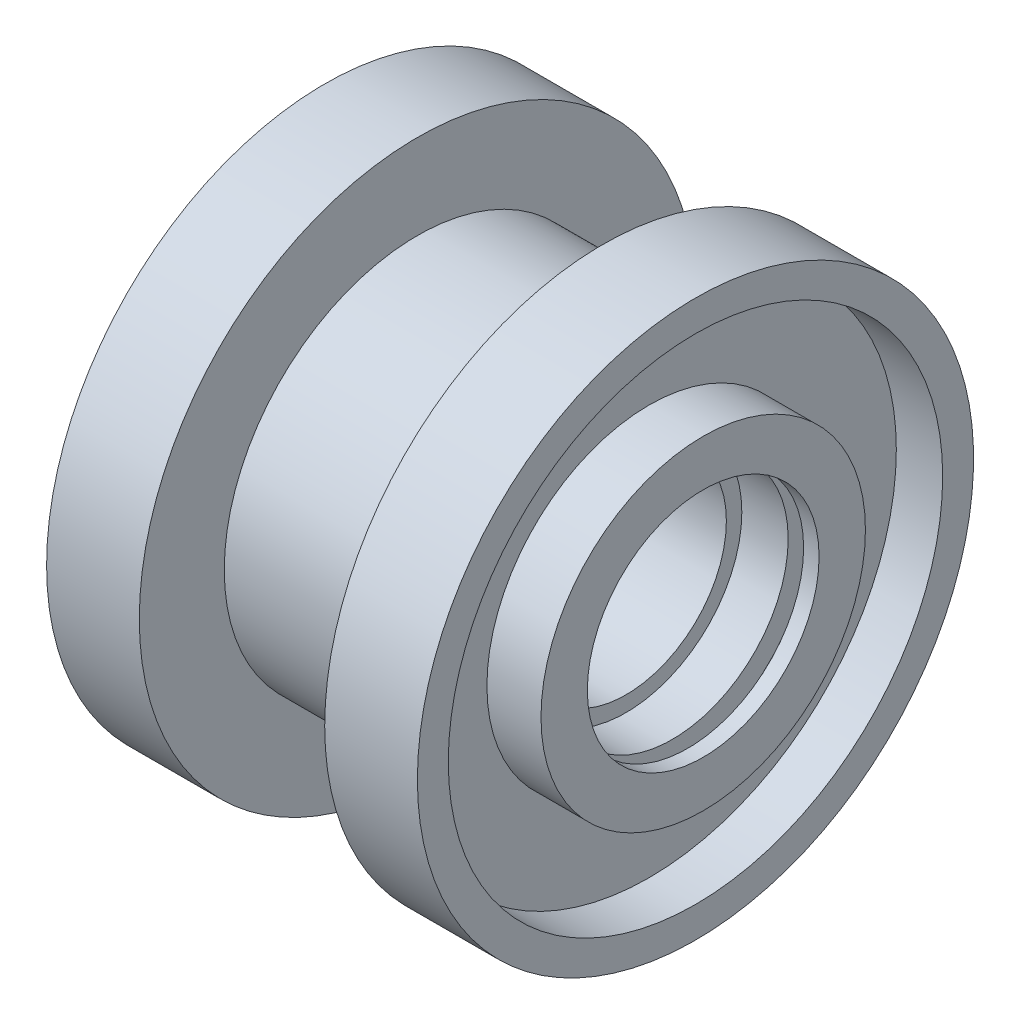
SolidWorks part; units mm, degrees
material "PS HI"
ref_plane "Płaszczyzna przednia" through (0, 0, 0) normal (0, 0, 1) x (1, 0, 0)
ref_plane "Płaszczyzna górna" through (0, 0, 0) normal (0, 1, 0) x (1, 0, 0)
ref_plane "Płaszczyzna prawa" through (0, 0, 0) normal (1, 0, 0) x (0, 0, -1)
sketch "Szkic1" plane through (0, 0, 0) normal (0, 0, 1) x (1, 0, 0)
  line L0 (-12.5, 0) -> (12.5, 0) construction
  line L1 (0, -18) -> (0, 18) construction
  line L2 (-6, 12.5) -> (6, 12.5)
  line L3 (6, 12.5) -> (6, 18)
  line L4 (6, 18) -> (12, 18)
  line L5 (12, 18) -> (12, 16)
  line L6 (12, 16) -> (9, 16)
  line L7 (9, 16) -> (9, 10.5)
  line L10 (-12, 16) -> (-9, 16)
  line L11 (-12, 18) -> (-12, 16)
  line L12 (-6, 18) -> (-12, 18)
  line L13 (-6, 12.5) -> (-6, 18)
  line L15 (12.5, 7.5) -> (12.5, 10.5)
  line L16 (12.5, 10.5) -> (9, 10.5)
  line L18 (-9, 16) -> (-9, 10.5)
  line L20 (-12.5, 7.5) -> (-12.5, 10.5)
  line L21 (-12.5, 10.5) -> (-9, 10.5)
  line L22 (12.5, 7.5) -> (11.5, 7.5)
  line L23 (7.5, 7.5) -> (7.5, 6.5)
  line L24 (7.5, 6.5) -> (-7.5, 6.5)
  line L25 (-7.5, 7.5) -> (-10.5, 7.5)
  line L26 (-7.5, 7.5) -> (-7.5, 6.5)
  line L27 (11.5, 7.5) -> (11.5, 8.9)
  line L28 (11.5, 8.9) -> (10.5, 8.9)
  line L29 (10.5, 8.9) -> (10.5, 7.5)
  line L30 (10.5, 7.5) -> (7.5, 7.5)
  line L31 (-11.5, 7.5) -> (-11.5, 8.9)
  line L32 (-10.5, 8.9) -> (-10.5, 7.5)
  line L33 (-11.5, 8.9) -> (-10.5, 8.9)
  line L34 (-11.5, 7.5) -> (-12.5, 7.5)
  point P1 (12, 17)
  point P7 (0, 0)
  point P14 (0, 7.5)
  point P15 (7.5, 7.5)
  point P21 (0, 12.5)
  point P23 (12.5, 9)
  point P32 (0, 6.5)
  dimension "D2" = 25
  dimension "D3" = 32
  dimension "D4" = 36
  dimension "D5" = 3
  dimension "D6" = 6
  dimension "D7" = 12
  dimension "D8" = 21
  dimension "D9" = 3.5
  dimension "D10" = 25
  dimension "D11" = 5
  dimension "D12" = 13
  dimension "D14" = 1
  dimension "D15" = 3
  dimension "D16" = 15
  dimension "D17" = 17.8
revolve "Obrót1" add sketch "Szkic1" angle 360 about L0
sketch "Szkic2" plane through (-12, 0, 0) normal (-1, 0, 0) x (0, 0, 1)
  line L0 (0, 18) -> (0, 16) construction
  circle A0 centre (0, 17) radius 0.5
  dimension "D1" = 1
extrude "Wytnij-wyciągnięcie1" cut sketch "Szkic2" against normal blind 1
